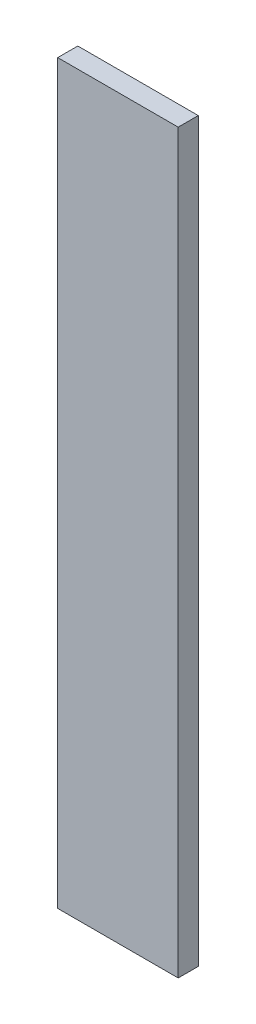
SolidWorks part; units mm, degrees
ref_plane "Front Plane" through (0, 0, 0) normal (0, 0, 1) x (1, 0, 0)
ref_plane "Top Plane" through (0, 0, 0) normal (0, 1, 0) x (1, 0, 0)
ref_plane "Right Plane" through (0, 0, 0) normal (1, 0, 0) x (0, 0, -1)
sketch "Sketch1" plane through (0, 0, 0) normal (0, 0, 1) x (1, 0, 0)
  line L1 (-15, -91.75) -> (15, -91.75)
  line L2 (-15, -91.75) -> (-15, 91.75)
  line L3 (-15, 91.75) -> (15, 91.75)
  line L4 (15, -91.75) -> (15, 91.75)
  line L5 (-15, -91.75) -> (15, 91.75) construction
  line L6 (-15, 91.75) -> (15, -91.75) construction
  point P0 (0, 0)
  dimension "D1" = 30
  dimension "D2" = 183.5
extrude "Boss-Extrude1" add sketch "Sketch1" along normal blind 5
